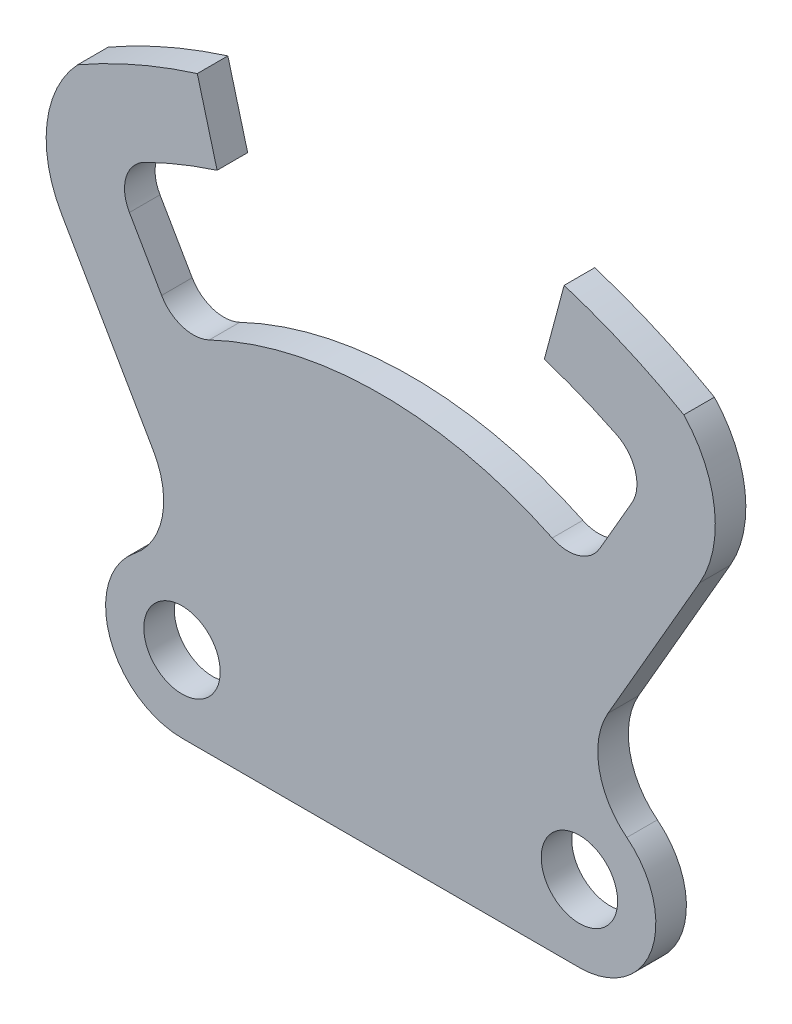
SolidWorks part; units mm, degrees
ref_plane "Alzado" through (0, 0, 0) normal (0, 0, 1) x (1, 0, 0)
ref_plane "Planta" through (0, 0, 0) normal (0, 1, 0) x (1, 0, 0)
ref_plane "Vista lateral" through (0, 0, 0) normal (1, 0, 0) x (0, 0, -1)
sketch "Croquis1" plane through (0, 0, 0) normal (0, 0, 1) x (1, 0, 0)
  line L0 (0, 0) -> (0, 210.9996) construction
  line L1 (-65, 0) -> (65, 0)
  line L2 (74.3489, 76.7305) -> (104.3489, 128.692)
  line L3 (71.6733, 122.0962) -> (82.2007, 140.3303)
  line L4 (53.5227, 166.6143) -> (60, 190.7878)
  line L5 (-74.3489, 76.7305) -> (-104.3489, 128.692)
  line L6 (-53.5227, 166.6143) -> (-60, 190.7878)
  line L7 (-71.6733, 122.0962) -> (-82.2007, 140.3303)
  arc A0 (99.1537, 173.6909) -> (60, 190.7878) centre (0, 0) ccw
  arc A1 (77.0949, 157.1031) -> (53.5227, 166.6143) centre (0, 0) ccw
  arc A2 (56.1023, 117.2712) -> (-56.1023, 117.2712) centre (0, 0) ccw
  circle A3 centre (65, 25) radius 12.5
  arc A4 (65, 0) -> (80.4998, 44.6152) centre (65, 25) ccw
  arc A5 (80.4998, 44.6152) -> (74.3489, 76.7305) centre (95.9995, 64.2305) cw
  arc A6 (104.3489, 128.692) -> (99.1537, 173.6909) centre (71.4399, 147.692) ccw
  arc A7 (71.6733, 122.0962) -> (56.1023, 117.2712) centre (61.281, 128.0962) cw
  arc A8 (82.2007, 140.3303) -> (77.0949, 157.1031) centre (71.8084, 146.3303) ccw
  arc A9 (-65, 0) -> (-80.4998, 44.6152) centre (-65, 25) cw
  circle A10 centre (-65, 25) radius 12.5
  arc A11 (-80.4998, 44.6152) -> (-74.3489, 76.7305) centre (-95.9995, 64.2305) ccw
  arc A12 (-104.3489, 128.692) -> (-99.1537, 173.6909) centre (-71.4399, 147.692) cw
  arc A13 (-99.1537, 173.6909) -> (-60, 190.7878) centre (0, 0) cw
  arc A14 (-77.0949, 157.1031) -> (-53.5227, 166.6143) centre (0, 0) cw
  arc A15 (-82.2007, 140.3303) -> (-77.0949, 157.1031) centre (-71.8084, 146.3303) cw
  arc A16 (-71.6733, 122.0962) -> (-56.1023, 117.2712) centre (-61.281, 128.0962) ccw
  dimension "D2" = 12
  dimension "D3" = 130
  dimension "D4" = 175
  dimension "D5" = 25
  dimension "D6" = 25
  dimension "D7" = 25
  dimension "D9" = 38
  dimension "D12" = 200
  dimension "D1" = 65
  dimension "D8" = 60
  dimension "D10" = 60
  dimension "D11" = 15
  dimension "D13" = 15
  dimension "D14" = 25
  dimension "D15" = 112.4878
extrude "Saliente-Extruir3" add sketch "Croquis1" along normal blind 10
